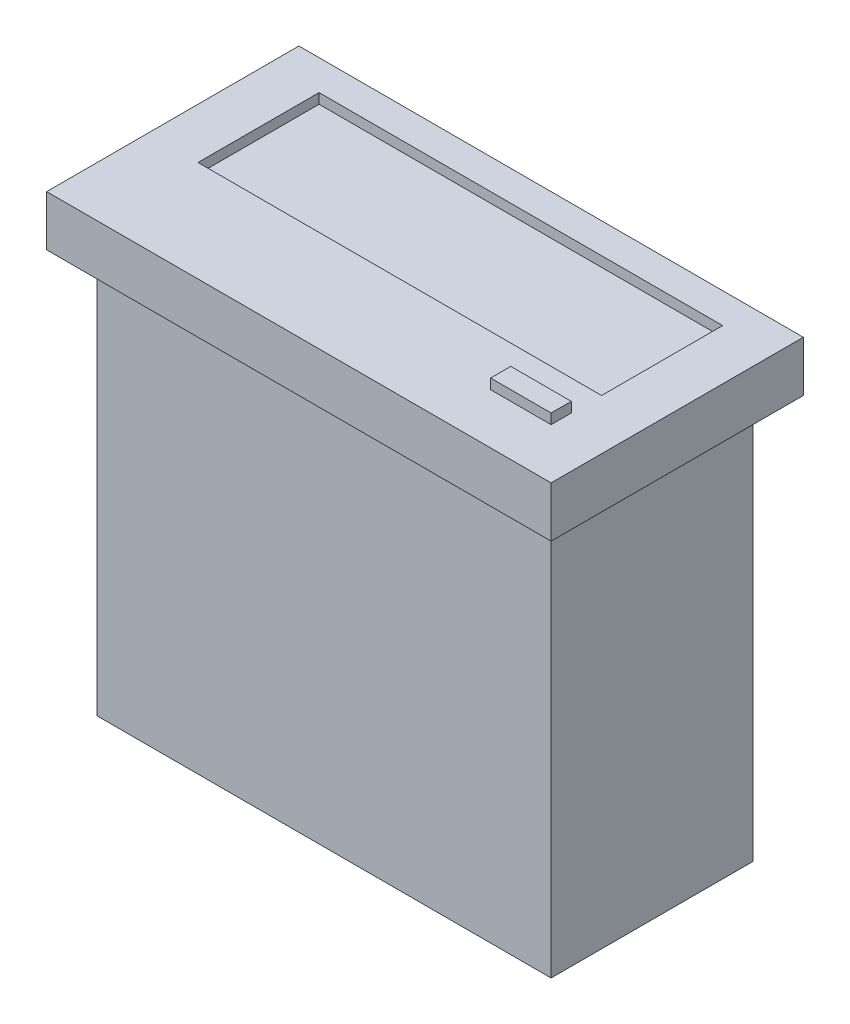
SolidWorks part; units mm, degrees
material "POM"
ref_plane "Front" through (0, 0, 0) normal (0, 0, 1) x (1, 0, 0)
ref_plane "Top" through (0, 0, 0) normal (0, 1, 0) x (1, 0, 0)
ref_plane "Right" through (0, 0, 0) normal (1, 0, 0) x (0, 0, -1)
sketch "Sketch1" plane through (0, 0, 0) normal (0, 1, 0) x (1, 0, 0)
  line L1 (0, 0) -> (50, 0)
  line L2 (0, 0) -> (0, 25)
  line L3 (0, 25) -> (50, 25)
  line L4 (50, 0) -> (50, 25)
  dimension "D1" = 50
  dimension "D2" = 25
extrude "Boss-Extrude1" add sketch "Sketch1" against normal blind 5
sketch "Sketch2" plane through (0, -5, 0) normal (0, -1, 0) x (1, 0, 0)
  line L0 (0, 0) -> (50, 0) construction
  line L1 (2.5, -2.5) -> (47.5, -2.5)
  line L2 (2.5, -2.5) -> (2.5, -22.5)
  line L3 (2.5, -22.5) -> (47.5, -22.5)
  line L4 (47.5, -2.5) -> (47.5, -22.5)
  line L5 (0, -25) -> (0, 0) construction
  point P4 (2.5, -12.5)
  point P7 (25, -22.5)
  dimension "D1" = 45
  dimension "D2" = 20
  dimension "D3" = 12.5
  dimension "D4" = 25
extrude "Boss-Extrude2" add sketch "Sketch2" along normal blind 40
sketch "Sketch3" plane through (0, 0, 0) normal (0, 1, 0) x (1, 0, 0)
  line L0 (0, 25) -> (0, 0) construction
  line L1 (5, 10) -> (45, 10)
  line L2 (5, 10) -> (5, 22)
  line L3 (5, 22) -> (45, 22)
  line L4 (45, 10) -> (45, 22)
  line L5 (50, 25) -> (0, 25) construction
  point P4 (25, 10)
  dimension "D1" = 40
  dimension "D2" = 25
  dimension "D3" = 3
  dimension "D4" = 12
extrude "Cut-Extrude1" cut sketch "Sketch3" against normal blind 1
sketch "Sketch4" plane through (0, 0, 0) normal (0, 1, 0) x (1, 0, 0)
  line L0 (50, 0) -> (50, 25) construction
  line L1 (39, 7) -> (45, 7)
  line L2 (39, 7) -> (39, 5)
  line L3 (39, 5) -> (45, 5)
  line L4 (45, 7) -> (45, 5)
  line L5 (0, 0) -> (50, 0) construction
  point P4 (45, 6)
  dimension "D1" = 5
  dimension "D2" = 2
  dimension "D3" = 6
  dimension "D4" = 5
extrude "Boss-Extrude3" add sketch "Sketch4" along normal blind 1
